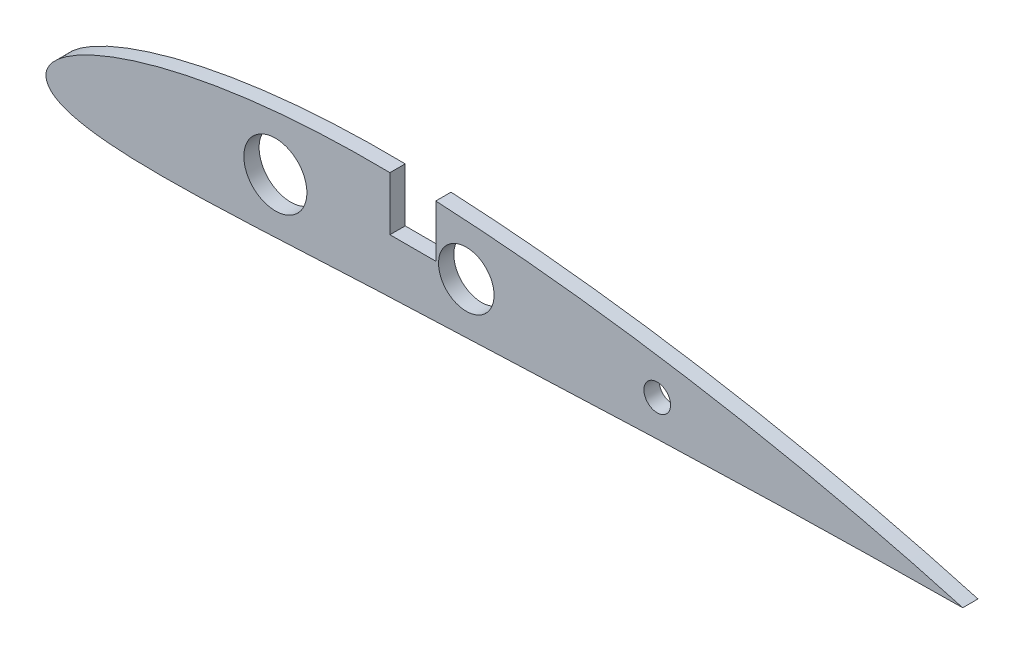
SolidWorks part; units mm, degrees
ref_plane "前视基准面" through (0, 0, 0) normal (0, 0, 1) x (1, 0, 0)
ref_plane "上视基准面" through (0, 0, 0) normal (0, 1, 0) x (1, 0, 0)
ref_plane "右视基准面" through (0, 0, 0) normal (1, 0, 0) x (0, 0, -1)
sketch "草图1" plane through (0, 0, 0) normal (0, 0, 1) x (1, 0, 0)
  spline S0 degree 3 poles (0, 0) (-0.0053, 0.0273) (-0.0128, 0.0659) (-0.0222, 0.1207) (-0.0302, 0.1709) (-0.0405, 0.2419) (-0.0527, 0.3427) (-0.0654, 0.486) (-0.0744, 0.6901) (-0.0687, 0.982) (-0.033, 1.3122) (0.0306, 1.6356) (0.1216, 1.9769) (0.2504, 2.3423) (0.4723, 2.8385) (0.7731, 3.3705) (1.1616, 3.9312) (1.5594, 4.4281) (2.0917, 5.0225) (2.7778, 5.6923) (3.6273, 6.4188) (4.7647, 7.2947) (6.2175, 8.278) (7.9975, 9.3366) (9.7956, 10.2986) (11.6087, 11.1847) (13.4346, 12.0081) (15.2715, 12.7783) (17.7295, 13.7414) (20.8254, 14.8433) (24.5719, 16.0302) (28.3396, 17.0985) (32.1249, 18.0618) (35.9251, 18.9298) (39.7379, 19.7103) (43.5615, 20.4093) (47.394, 21.0318) (51.2341, 21.5819) (55.0804, 22.063) (58.9319, 22.4783) (62.7875, 22.8303) (66.6463, 23.1214) (70.5074, 23.3536) (74.3702, 23.5288) (78.2337, 23.6486) (82.0975, 23.7147) (85.961, 23.7283) (89.8234, 23.6907) (93.6764, 23.6042) (98.7737, 23.421) (105.1142, 23.1127) (112.7023, 22.6287) (120.2837, 22.0343) (127.8572, 21.3355) (135.422, 20.5364) (142.9771, 19.6411) (150.5219, 18.6527) (158.0556, 17.574) (165.5776, 16.4069) (173.0873, 15.1531) (180.584, 13.8138) (188.067, 12.3897) (195.5358, 10.8809) (202.9897, 9.2875) (210.4278, 7.6086) (217.8495, 5.8438) (225.2534, 3.9897) (232.6408, 2.0527) (237.5464, 0.6844) (240, 0) knots 0 0 0 0 0.000335 0.000473 0.000669 0.000946 0.001337 0.001891 0.002677 0.003795 0.005403 0.006667 0.007758 0.009653 0.011323 0.014296 0.016992 0.019526 0.021952 0.026593 0.031054 0.035399 0.043867 0.05215 0.060317 0.068405 0.076436 0.084423 0.092377 0.108208 0.123966 0.139672 0.155338 0.170974 0.186587 0.202179 0.217755 0.233318 0.248869 0.26441 0.279943 0.295468 0.310986 0.326499 0.342007 0.357511 0.37301 0.388507 0.404002 0.419397 0.449899 0.480404 0.510914 0.541428 0.571947 0.60247 0.632999 0.663532 0.694072 0.724618 0.755171 0.785732 0.816302 0.846882 0.877474 0.90808 0.938701 0.969341 1 1 1 1
  spline S1 degree 3 poles (240, 0) (234.9171, -0.0576) (224.7756, -0.1725) (209.598, -0.4159) (194.487, -0.7282) (179.4363, -1.1195) (164.4405, -1.5883) (149.4943, -2.1277) (134.5923, -2.7228) (119.7285, -3.3492) (107.3626, -3.8736) (97.5148, -4.2614) (87.7603, -4.6454) (75.6228, -5.2308) (63.4871, -5.8552) (53.7559, -6.3201) (46.4241, -6.6281) (39.054, -6.8652) (32.8806, -6.9674) (27.9105, -6.9577) (24.1513, -6.8907) (20.3631, -6.7452) (17.1862, -6.536) (14.6256, -6.2932) (12.6835, -6.0627) (10.7231, -5.7715) (8.7382, -5.3995) (7.0706, -4.998) (5.7219, -4.5932) (4.684, -4.2275) (3.813, -3.8587) (3.1074, -3.5055) (2.5588, -3.1937) (1.9932, -2.8205) (1.5174, -2.4421) (1.1261, -2.0678) (0.8689, -1.7792) (0.6552, -1.4986) (0.4731, -1.2242) (0.3138, -0.933) (0.1966, -0.6656) (0.1265, -0.4738) (0.0832, -0.3366) (0.0557, -0.2389) (0.0378, -0.1693) (0.026, -0.1199) (0.0136, -0.0658) (0.0056, -0.0272) (0, 0) knots 0 0 0 0 0.062943 0.125585 0.18796 0.250094 0.312012 0.373735 0.435285 0.496682 0.557949 0.588544 0.618717 0.678827 0.73901 0.769186 0.79946 0.829874 0.860492 0.875906 0.891415 0.907045 0.922844 0.93083 0.938892 0.947058 0.955366 0.963892 0.968281 0.972798 0.977512 0.979981 0.982565 0.985321 0.988365 0.990077 0.992022 0.993143 0.994443 0.996096 0.997246 0.998054 0.998624 0.999027 0.999312 0.999513 0.999656 1 1 1 1
extrude "凸台-拉伸1" add sketch "草图1" along normal blind 4
ref_plane "基准面1" through (0, 0, 4) normal (0, 0, 1) x (1, 0, 0)
sketch "草图2" plane through (0, 0, 4) normal (0, 0, 1) x (1, 0, 0)
  circle A0 centre (60, 8.25) radius 8.258
extrude "切除-拉伸1" cut sketch "草图2" against normal through all
sketch "草图3" plane through (0, 0, 4) normal (0, 0, 1) x (1, 0, 0)
  circle A0 centre (110, 9.5093) radius 7.273
extrude "切除-拉伸2" cut sketch "草图3" against normal through all
sketch "草图4" plane through (0, 0, 4) normal (0, 0, 1) x (1, 0, 0)
  circle A0 centre (160, 7.7037) radius 3.493
extrude "切除-拉伸3" cut sketch "草图4" against normal through all
sketch "草图6" plane through (0, 0, 0) normal (0, 0, 1) x (1, 0, 0)
  line L0 (90, 9.6) -> (102, 9.6)
  line L1 (102, 9.6) -> (102, 25.6)
  line L2 (102, 25.6) -> (90, 25.6)
  line L3 (90, 25.6) -> (90, 9.6)
extrude "切除-拉伸5" cut sketch "草图6" against normal mid plane 482.148
